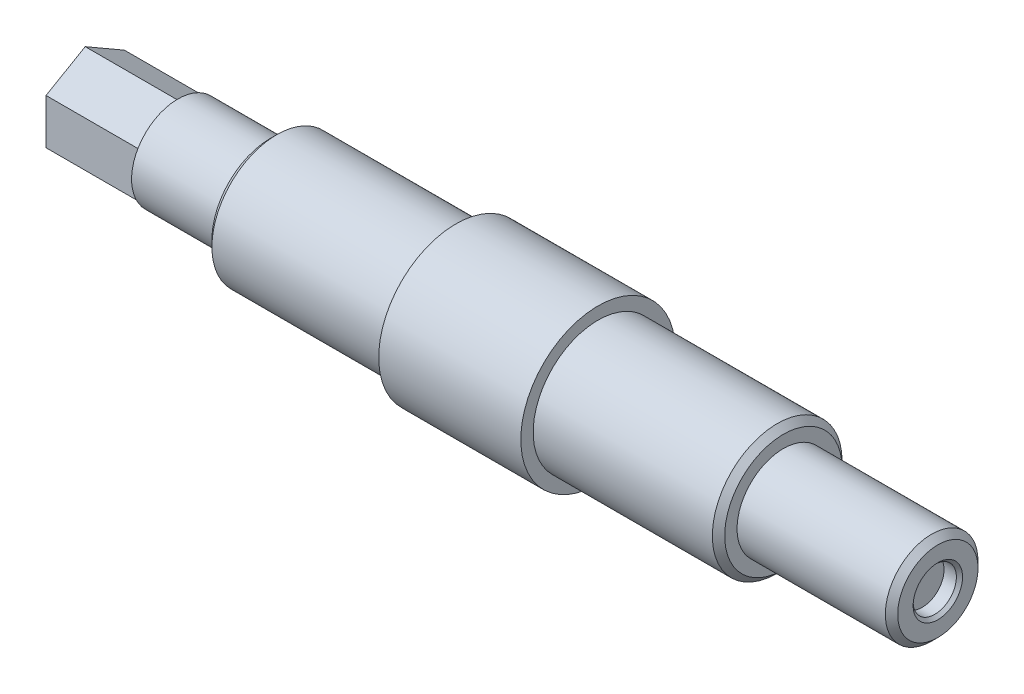
SolidWorks part; units mm, degrees
ref_plane "Front" through (0, 0, 0) normal (0, 0, 1) x (1, 0, 0)
ref_plane "Top" through (0, 0, 0) normal (0, 1, 0) x (1, 0, 0)
ref_plane "Right" through (0, 0, 0) normal (1, 0, 0) x (0, 0, -1)
sketch "草图1" plane through (0, 0, 0) normal (1, 0, 0) x (0, 0, -1)
  line L0 (0, 0) -> (0, 2) construction
  line L1 (0, -7.3323) -> (6.35, -3.6662)
  line L2 (6.35, -3.6662) -> (6.35, 3.6662)
  line L3 (6.35, 3.6662) -> (0, 7.3323)
  line L4 (0, 7.3323) -> (-6.35, 3.6662)
  line L5 (-6.35, 3.6662) -> (-6.35, -3.6662)
  line L6 (-6.35, -3.6662) -> (0, -7.3323)
  circle A0 centre (0, 0) radius 7.3323 construction
  dimension "D1" = 60
  dimension "D2" = 12.7
extrude "凸台-拉伸1" add sketch "草图1" along normal blind 15
hole_wizard "M5x0.8 螺纹孔1" positions "草图3" profile "草图4" tap size "M5x0.8" standard "ANSI Metric"
sketch "草图3" plane through (0, 0, 0) normal (-1, 0, 0) x (0, 0, 1)
  point P0 (0, 0)
sketch "草图4" plane through (0, 0, 0) normal (0, 1, 0) x (0, 0, 1)
  line L0 (0, 0) -> (0, 13.6618)
  line L1 (0, 13.6618) -> (2.1, 12.4)
  line L2 (2.1, 12.4) -> (2.1, 0)
  line L5 (2.1, 0) -> (0, 0)
  line L10 (0, 13.6618) -> (-2.1, 12.4) construction
  line L11 (0, -6.35) -> (0, 107.95) construction
  dimension "螺纹孔钻头直径" = 4.2
  dimension "螺纹孔钻头深度" = 12.4
  dimension "导头角度" = 118
cosmetic thread "孔螺蚊线1" parameters "D1"=10, "D2"=5
sketch "草图5" plane through (15, 0, 0) normal (1, 0, 0) x (0, 0, -1)
  circle A0 centre (0, 0) radius 7.5
extrude "凸台-拉伸2" add sketch "草图5" along normal blind 15
sketch "草图6" plane through (30, 0, 0) normal (1, 0, 0) x (0, 0, -1)
  circle A0 centre (0, 0) radius 10.5
extrude "凸台-拉伸3" add sketch "草图6" along normal blind 30
sketch "草图7" plane through (60, 0, 0) normal (1, 0, 0) x (0, 0, -1)
  circle A0 centre (0, 0) radius 12.5
extrude "凸台-拉伸4" add sketch "草图7" along normal blind 23
sketch "草图8" plane through (83, 0, 0) normal (1, 0, 0) x (0, 0, -1)
  circle A0 centre (0, 0) radius 10.5
extrude "凸台-拉伸5" add sketch "草图8" along normal blind 30
chamfer "倒角1" distance 1 angle 45 1 edges at (30, 0, -10.5)
chamfer "倒角2" distance 1 angle 45 1 edges at (113, 0, -10.5)
sketch "草图9" plane through (113, 0, 0) normal (1, 0, 0) x (0, 0, -1)
  circle A0 centre (0, 0) radius 7.5
extrude "凸台-拉伸6" add sketch "草图9" along normal blind 25
chamfer "倒角3" distance 1 angle 45 1 edges at (138, 0, -7.5)
sketch "草图10" plane through (138, 0, 0) normal (1, 0, 0) x (0, 0, -1)
  circle A0 centre (0, 0) radius 3.5
extrude "切除-拉伸1" cut sketch "草图10" against normal blind 2.5
chamfer "倒角4" distance 0.5 angle 45 1 edges at (138, 0, -3.5)
